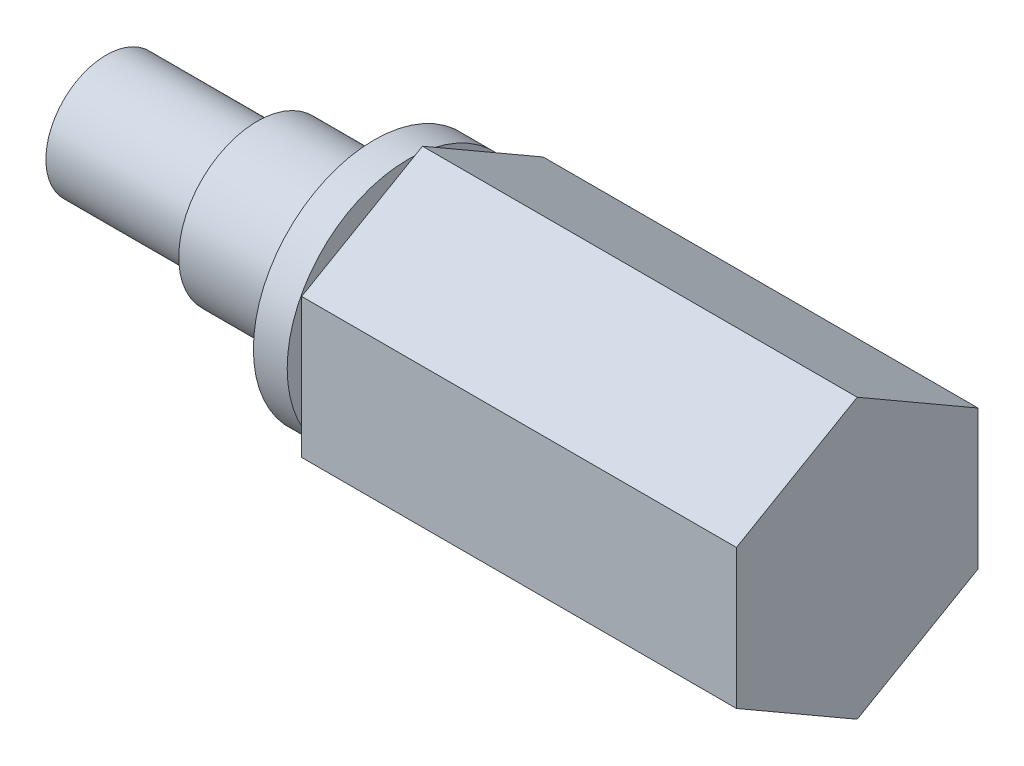
SolidWorks part; units mm, degrees
material "6061 Alloy"
ref_plane "Front Plane" through (0, 0, 0) normal (0, 0, 1) x (1, 0, 0)
ref_plane "Top Plane" through (0, 0, 0) normal (0, 1, 0) x (1, 0, 0)
ref_plane "Right Plane" through (0, 0, 0) normal (1, 0, 0) x (0, 0, -1)
sketch "Sketch1" plane through (0, 0, 0) normal (0, 0, 1) x (1, 0, 0)
  line L0 (0, 0) -> (-17809.1409, 0) construction
  line L1 (0, 0) -> (0, 6.35)
  line L2 (0, 6.35) -> (-22.86, 6.35)
  line L3 (-22.86, 6.35) -> (-22.86, 5.2417)
  line L4 (-22.86, 5.2417) -> (-23.622, 5.2417)
  line L5 (-23.622, 5.2417) -> (-23.622, 6.35)
  line L6 (-23.622, 6.35) -> (-25.4, 6.35)
  line L7 (-25.4, 6.35) -> (-25.4, 4.1275)
  line L8 (-25.4, 4.1275) -> (-31.5468, 4.1275)
  line L9 (-31.5468, 4.1275) -> (-31.5468, 3.175)
  line L10 (-31.5468, 3.175) -> (-39.4843, 3.175)
  line L11 (-39.4843, 3.175) -> (-39.4843, 0)
  line L12 (-39.4843, 0) -> (0, 0)
  point P16 (-32.4997, 4.8173)
  point P17 (-29.1283, 5.2139)
  point P18 (0, 8.9159)
  point P19 (-31.5118, 5.2417)
  dimension "D1" = 6.35
  dimension "D2" = 8.255
  dimension "D3" = 12.7
  dimension "D4" = 2.54
  dimension "D5" = 7.9375
  dimension "D6" = 0.762
  dimension "D7" = 22.86
  dimension "D8" = 8.6868
revolve "Revolve1" add sketch "Sketch1" angle 360 about L0
sketch "Sketch2" plane through (0, 0, 0) normal (1, 0, 0) x (0, 0, -1)
  line L1 (-6.35, 3.6662) -> (-6.35, -3.6662)
  line L2 (-6.35, -3.6662) -> (0, -7.3323)
  line L3 (0, -7.3323) -> (6.35, -3.6662)
  line L4 (6.35, -3.6662) -> (6.35, 3.6662)
  line L5 (6.35, 3.6662) -> (0, 7.3323)
  line L6 (0, 7.3323) -> (-6.35, 3.6662)
  circle A0 centre (0, 0) radius 6.35 construction
  circle A1 centre (0, 0) radius 6.35 construction
extrude "Boss-Extrude1" add sketch "Sketch2" against normal up to surface (22.86 mm away) up to face at (-22.86, 0, -5.2417)
